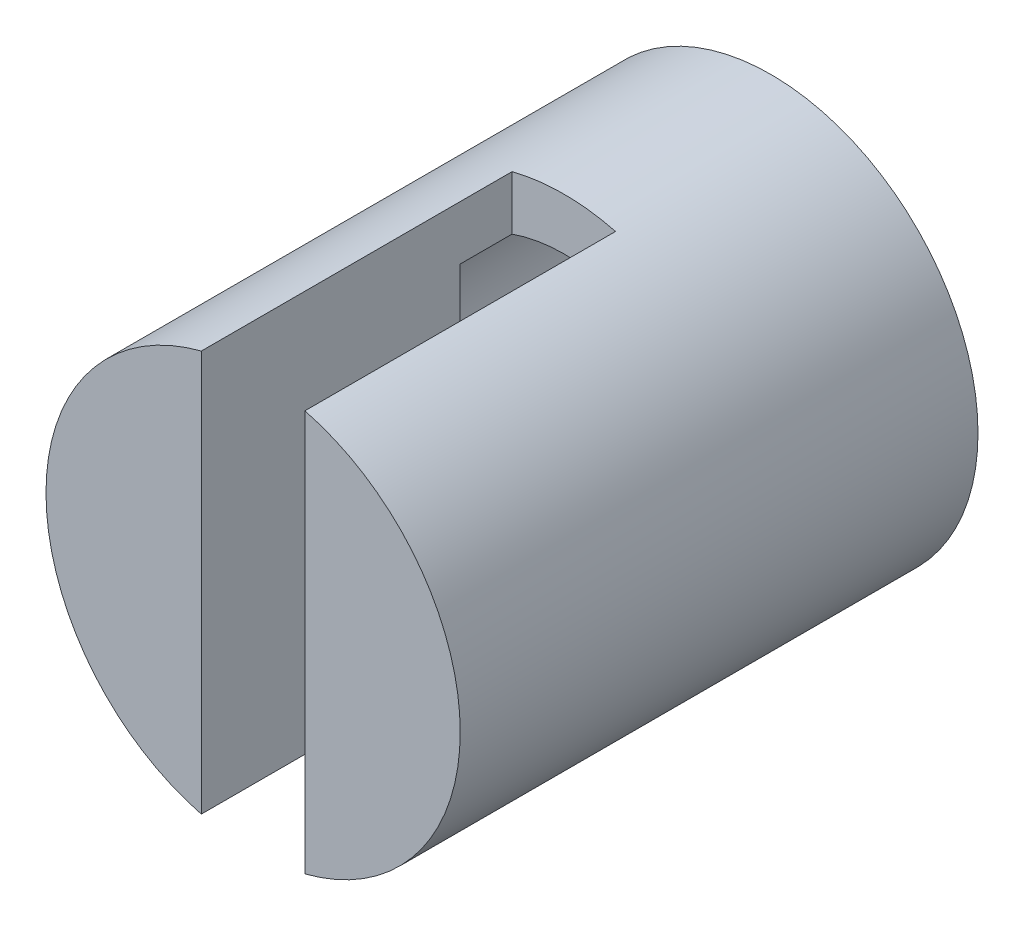
SolidWorks part; units mm, degrees
ref_plane "Alzado" through (0, 0, 0) normal (0, 0, 1) x (1, 0, 0)
ref_plane "Planta" through (0, 0, 0) normal (0, 1, 0) x (1, 0, 0)
ref_plane "Vista lateral" through (0, 0, 0) normal (1, 0, 0) x (0, 0, -1)
sketch "Croquis1" plane through (0, 0, 0) normal (0, 0, 1) x (1, 0, 0)
  circle A0 centre (0, 44.6491) radius 4
  dimension "D1" = 8
extrude "Saliente-Extruir1" add sketch "Croquis1" against normal blind 10 contours A0
sketch "Croquis2" plane through (0, 0, 0) normal (0, 0, 1) x (1, 0, 0)
  line L1 (-1, 38.1192) -> (1, 38.1192)
  line L2 (-1, 38.1192) -> (-1, 51.179)
  line L3 (-1, 51.179) -> (1, 51.179)
  line L4 (1, 38.1192) -> (1, 51.179)
  line L5 (-1, 38.1192) -> (1, 51.179) construction
  line L6 (-1, 51.179) -> (1, 38.1192) construction
  point P0 (0, 44.6491)
  dimension "D1" = 2
extrude "Cortar-Extruir1" cut sketch "Croquis2" against normal blind 6
sketch "Croquis3" plane through (0, 0, -10) normal (0, 0, -1) x (-1, 0, 0)
  circle A0 centre (0, 44.6491) radius 3
  dimension "D1" = 6
extrude "Cortar-Extruir2" cut sketch "Croquis3" against normal blind 5
